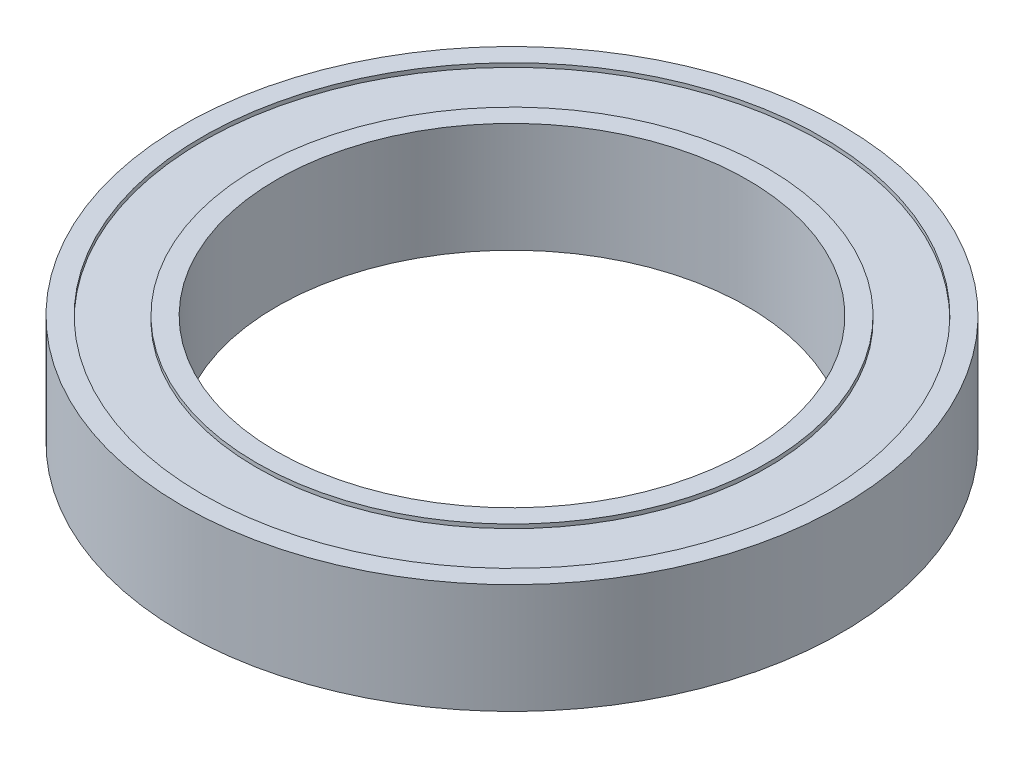
SolidWorks part; units mm, degrees
ref_plane "Front Plane" through (0, 0, 0) normal (0, 0, 1) x (1, 0, 0)
ref_plane "Top Plane" through (0, 0, 0) normal (0, 1, 0) x (1, 0, 0)
ref_plane "Right Plane" through (0, 0, 0) normal (1, 0, 0) x (0, 0, -1)
sketch "Sketch1" plane through (0, 0, 0) normal (0, 1, 0) x (1, 0, 0)
  circle A0 centre (0, 0) radius 15
  circle A1 centre (0, 0) radius 21
  dimension "D1" = 30
  dimension "D2" = 42
extrude "Boss-Extrude1" add sketch "Sketch1" along normal blind 7
sketch "Sketch2" plane through (0, 7, 0) normal (0, 1, 0) x (1, 0, 0)
  circle A2 centre (0, 0) radius 19.73
  circle A3 centre (0, 0) radius 19.73
  circle A5 centre (0, 0) radius 16.27
  circle A6 centre (0, 0) radius 16.27
  dimension "D1" = 1.27
  dimension "D2" = 1.27
extrude "Cut-Extrude1" cut sketch "Sketch2" against normal blind 0.254
ref_plane "Plane1" through (0, 3.5, 0) normal (0, -1, 0) x (-1, 0, 0)
mirror "Mirror1" about plane through (0, 3.5, 0) normal (0, -1, 0) of "Cut-Extrude1"
